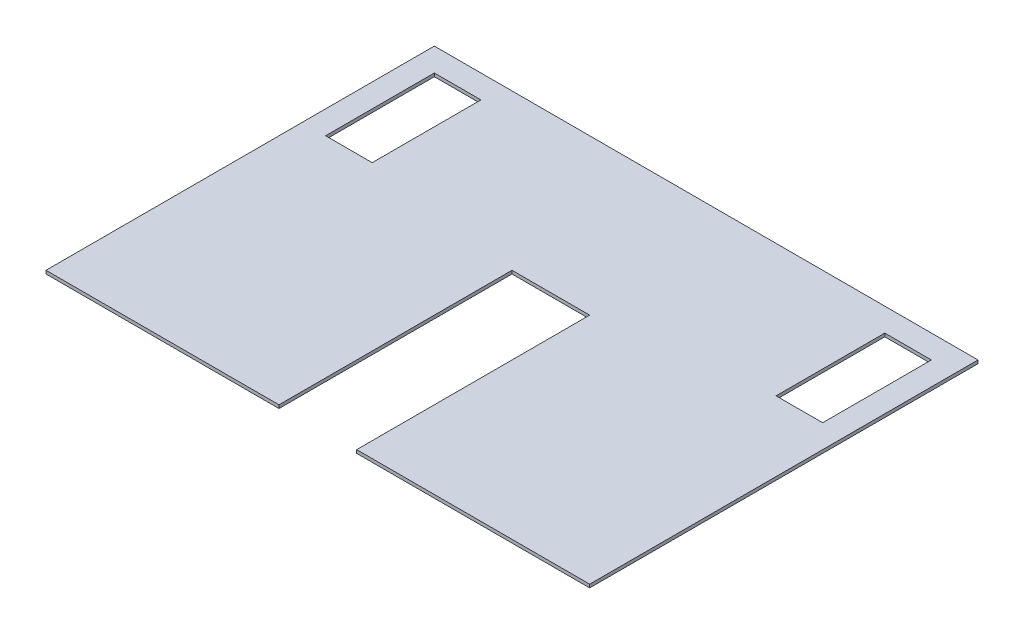
SolidWorks part; units mm, degrees
material "Plain Carbon Steel"
ref_plane "Front" through (0, 0, 0) normal (0, 0, 1) x (1, 0, 0)
ref_plane "Top" through (0, 0, 0) normal (0, 1, 0) x (1, 0, 0)
ref_plane "Right" through (0, 0, 0) normal (1, 0, 0) x (0, 0, -1)
sketch "Sketch1" plane through (0, 0, 0) normal (0, 1, 0) x (1, 0, 0)
  line L1 (0, 0) -> (-177.8, 0)
  line L2 (0, 0) -> (0, 127)
  line L3 (0, 127) -> (-177.8, 127)
  line L4 (-177.8, 0) -> (-177.8, 127)
  dimension "D1" = 177.8
  dimension "D2" = 127
extrude "Boss-Extrude1" add sketch "Sketch1" along normal blind 1.0668
sketch "Sketch2" plane through (0, 1.0668, 0) normal (0, 1, 0) x (1, 0, 0)
  line L0 (-101.6, 82.55) -> (-101.6, 0) construction
  line L3 (-76.2, 82.55) -> (-76.2, 0) construction
  line L6 (-177.8, 0) -> (0, 0) construction
  line L10 (-24.13, 127) -> (-24.13, 76.2) construction
  line L15 (-24.13, 82.55) -> (0, 82.55) construction
  line L21 (-6.35, 120.65) -> (-6.35, 82.55) construction
  line L28 (0, 120.65) -> (-24.13, 120.65) construction
  line L36 (-177.8, 82.55) -> (-153.67, 82.55) construction
  line L45 (-171.45, 120.65) -> (-171.45, 82.55) construction
  line L55 (-153.67, 76.2) -> (-153.67, 127) construction
  line L66 (-153.67, 120.65) -> (-177.8, 120.65) construction
  line L78 (-171.45, 120.65) -> (-171.45, 82.55) construction
  line L79 (-171.45, 82.55) -> (-153.67, 82.55) construction
  line L80 (-153.67, 82.55) -> (-153.67, 120.65) construction
  line L81 (-153.67, 120.65) -> (-171.45, 120.65) construction
  line L82 (-101.6, 76.2) -> (-101.6, 0)
  line L83 (-76.2, 76.2) -> (-76.2, 0)
  line L84 (-101.6, 76.2) -> (-76.2, 76.2)
  line L85 (-101.6, 0) -> (-76.2, 0)
  line L86 (-6.35, 120.65) -> (-6.35, 82.55) construction
  line L87 (-24.13, 120.65) -> (-24.13, 82.55) construction
  line L88 (-24.13, 82.55) -> (-6.35, 82.55) construction
  line L89 (-6.35, 120.65) -> (-24.13, 120.65) construction
  line L90 (-170.18, 83.82) -> (-154.94, 83.82)
  line L91 (-154.94, 83.82) -> (-154.94, 119.38)
  line L92 (-154.94, 119.38) -> (-170.18, 119.38)
  line L93 (-170.18, 119.38) -> (-170.18, 83.82)
  line L94 (-22.86, 119.38) -> (-22.86, 83.82)
  line L95 (-22.86, 83.82) -> (-7.62, 83.82)
  line L96 (-7.62, 119.38) -> (-7.62, 83.82)
  line L97 (-7.62, 119.38) -> (-22.86, 119.38)
  dimension "D1" = 1.27
extrude "Cut-Extrude1" cut sketch "Sketch2" against normal through all
